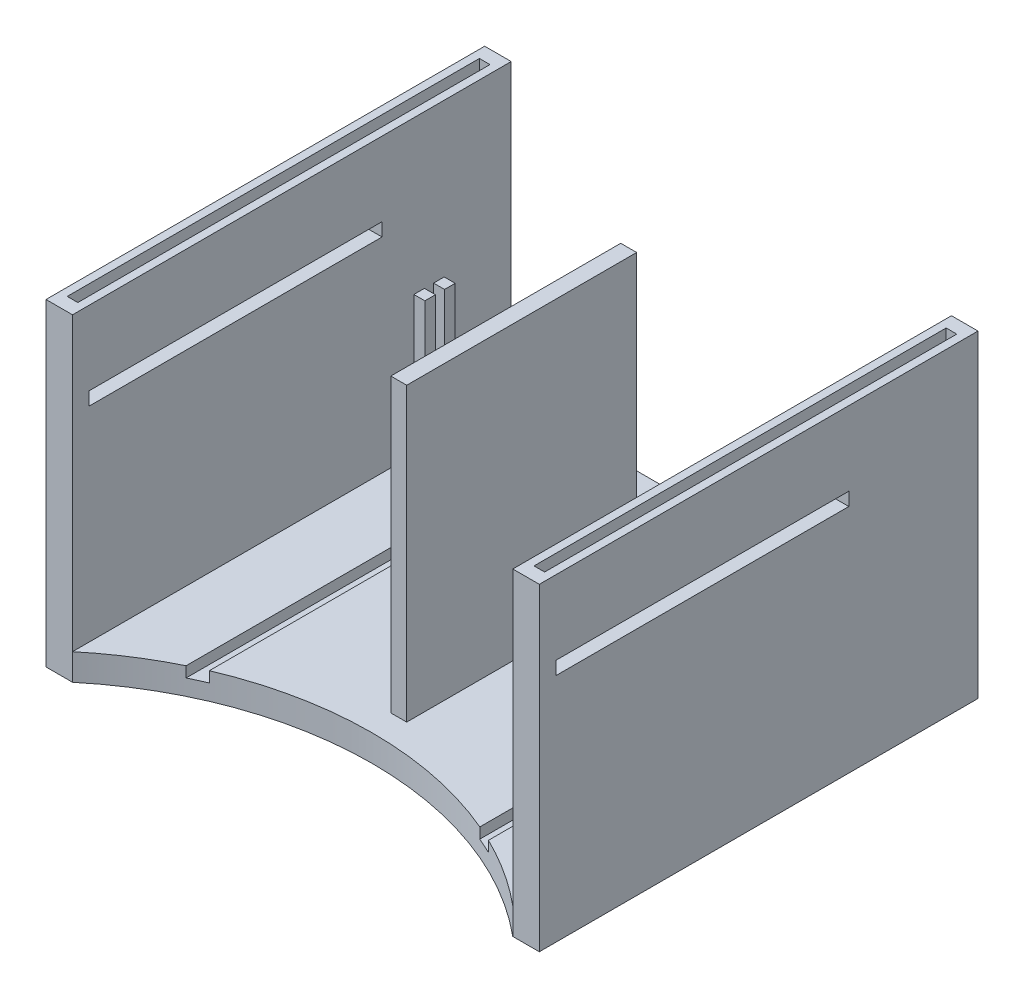
SolidWorks part; units mm, degrees
ref_plane "Front Plane" through (0, 0, 0) normal (0, 0, 1) x (1, 0, 0)
ref_plane "Top Plane" through (0, 0, 0) normal (0, 1, 0) x (1, 0, 0)
ref_plane "Right Plane" through (0, 0, 0) normal (1, 0, 0) x (0, 0, -1)
sketch "Sketch2" plane through (0, 0, 0) normal (0, 0, 1) x (1, 0, 0)
  line L0 (0, 0) -> (186, 0)
  line L1 (186, 0) -> (186, 120)
  line L2 (0, 0) -> (0, 120)
  dimension "D1" = 120
  dimension "D2" = 186
extrude "Extrude-Thin2" add sketch "Sketch2" along normal blind 165.4 thin thin type one direction wall 10
sketch "Sketch11" plane through (0, 10, 0) normal (0, 1, 0) x (1, 0, 0)
  line L0 (10, -165.4) -> (10, 0) construction
  line L1 (10, -32.703) -> (176, -32.703)
  line L2 (10, -32.703) -> (10, -36.703)
  line L3 (10, -36.703) -> (176, -36.703)
  line L4 (176, -32.703) -> (176, -36.703)
  line L6 (176, 0) -> (10, 0) construction
  dimension "D1" = 32.703
  dimension "D2" = 4
  dimension "D3" = 166
  dimension "D4" = 0
extrude "Boss-Extrude3" add sketch "Sketch11" along normal blind 2.6416
sketch "Sketch13" plane through (10, 0, 0) normal (1, 0, 0) x (0, 0, -1)
  line L0 (0, 120) -> (0, 0) construction
  line L1 (-159.195, 92.0516) -> (-48.7, 92.0516)
  line L2 (-159.195, 92.0516) -> (-159.195, 87.0516)
  line L3 (-159.195, 87.0516) -> (-48.7, 87.0516)
  line L4 (-48.7, 92.0516) -> (-48.7, 87.0516)
  line L6 (-165.4, 120) -> (-165.4, 0) construction
  line L7 (-165.4, 120) -> (0, 120) construction
  dimension "D1" = 5
  dimension "D2" = 6.205
  dimension "D3" = 48.7
  dimension "D4" = 27.9484
extrude "Cut-Extrude6" cut sketch "Sketch13" against normal through all both and the other way through all
sketch "Sketch14" plane through (0, 10, 0) normal (0, 1, 0) x (1, 0, 0)
  line L0 (176, -165.4) -> (10, -165.4)
  line L1 (93, -135.4) -> (10, -135.4) construction
  line L2 (10, -165.4) -> (10, -36.703) construction
  arc A0 (10, -165.4) -> (176, -165.4) centre (93, -265.2167) cw
  dimension "D1" = 30
extrude "Cut-Extrude7" cut sketch "Sketch14" against normal through all
sketch "Sketch19" plane through (0, 120, 0) normal (0, 1, 0) x (1, 0, 0)
  line L0 (10, -165.4) -> (10, -36.703) construction
  line L1 (3, -5) -> (7, -5)
  line L2 (3, -5) -> (3, -160.4)
  line L3 (3, -160.4) -> (7, -160.4)
  line L4 (7, -5) -> (7, -160.4)
  line L5 (0, -165.4) -> (0, 0) construction
  line L6 (0, 0) -> (10, 0) construction
  line L7 (0, -165.4) -> (10, -165.4) construction
  point P9 (5, 0)
  point P12 (5, -165.4)
  dimension "D1" = 3
  dimension "D2" = 3
  dimension "D3" = 5
  dimension "D4" = 5
extrude "Cut-Extrude9" cut sketch "Sketch19" against normal blind 10
sketch "Sketch20" plane through (0, 120, 0) normal (0, 1, 0) x (1, 0, 0)
  line L0 (186, -165.4) -> (186, 0) construction
  line L1 (179, -5) -> (183, -5)
  line L2 (179, -5) -> (179, -160.4)
  line L3 (179, -160.4) -> (183, -160.4)
  line L4 (183, -5) -> (183, -160.4)
  line L5 (176, -165.4) -> (176, 0) construction
  line L6 (176, 0) -> (186, 0) construction
  line L7 (176, -165.4) -> (186, -165.4) construction
  point P9 (181, 0)
  point P12 (181, -165.4)
  dimension "D1" = 3
  dimension "D2" = 3
  dimension "D3" = 5
  dimension "D4" = 5
extrude "Cut-Extrude10" cut sketch "Sketch20" against normal blind 10
sketch "Sketch21" plane through (0, 10, 0) normal (0, 1, 0) x (1, 0, 0)
  line L0 (176, -165.4) -> (176, -36.703) construction
  line L1 (90, -38.703) -> (96, -38.703)
  line L2 (90, -38.703) -> (90, -125.4)
  line L3 (90, -125.4) -> (96, -125.4)
  line L4 (96, -38.703) -> (96, -125.4)
  line L5 (10, -165.4) -> (10, 0) construction
  line L7 (10, -159.195) -> (10, -48.7) construction
  line L8 (10, -119.195) -> (176, -119.195) construction
  line L9 (10, -165.4) -> (10, -36.703) construction
  line L10 (0, -165.4) -> (10, -165.4) construction
  line L11 (10, -36.703) -> (176, -36.703) construction
  dimension "D1" = 80
  dimension "D2" = 80
  dimension "D3" = 40
  dimension "D4" = 46.205
  dimension "D5" = 2
extrude "Boss-Extrude4" add sketch "Sketch21" along direction (0, 1, 0) on the side of the normal through all
sketch "Sketch22" plane through (0, 10, 0) normal (0, 1, 0) x (1, 0, 0)
  line L0 (36, -48.703) -> (36, -148.5832)
  line L1 (36, -148.5832) -> (42, -145.8376)
  line L2 (42, -145.8376) -> (42, -48.703)
  line L3 (42, -48.703) -> (36, -48.703)
  line L4 (10, -36.703) -> (176, -36.703) construction
  line L6 (10, -159.195) -> (10, -48.7) construction
  line L7 (144, -145.8376) -> (150, -148.5832)
  line L8 (150, -148.5832) -> (150, -48.703)
  line L9 (150, -48.703) -> (144, -48.703)
  line L10 (144, -48.703) -> (144, -145.8376)
  line L11 (176, -165.4) -> (176, -36.703) construction
  arc A0 (176, -165.4) -> (10, -165.4) centre (93, -265.2167) ccw construction
  dimension "D1" = 6
  dimension "D2" = 26
  dimension "D3" = 6
  dimension "D4" = 26
  dimension "D5" = 12
extrude "Cut-Extrude11" cut sketch "Sketch22" against normal blind 4
sketch "Sketch23" plane through (0, 10, 0) normal (0, 1, 0) x (1, 0, 0)
  line L0 (10, -32.703) -> (10, 0) construction
  line L1 (10, -25.263) -> (176, -25.263)
  line L2 (10, -25.263) -> (10, -29.263)
  line L3 (10, -29.263) -> (176, -29.263)
  line L4 (176, -25.263) -> (176, -29.263)
  line L8 (176, -32.703) -> (10, -32.703) construction
  dimension "D1" = 3.44
  dimension "D2" = 166
  dimension "D3" = 0
  dimension "D4" = 4
extrude "Boss-Extrude5" add sketch "Sketch23" along normal blind 2.6416
sketch "Sketch24" plane through (0, 12.6416, 0) normal (0, 1, 0) x (1, 0, 0)
  line L0 (10, -29.263) -> (176, -29.263) construction
  line L1 (10, -25.263) -> (14.14, -25.263)
  line L2 (10, -25.263) -> (10, -29.263)
  line L3 (10, -29.263) -> (14.14, -29.263)
  line L4 (14.14, -25.263) -> (14.14, -29.263)
  dimension "D1" = 4.14
extrude "Boss-Extrude6" add sketch "Sketch24" along normal blind 49.64
sketch "Sketch25" plane through (0, 12.6416, 0) normal (0, 1, 0) x (1, 0, 0)
  line L0 (14.14, -29.263) -> (176, -29.263) construction
  line L1 (176, -25.263) -> (171.86, -25.263)
  line L2 (176, -25.263) -> (176, -29.263)
  line L3 (176, -29.263) -> (171.86, -29.263)
  line L4 (171.86, -25.263) -> (171.86, -29.263)
  dimension "D1" = 4.14
extrude "Boss-Extrude7" add sketch "Sketch25" along normal blind 49.64
sketch "Sketch26" plane through (0, 12.6416, 0) normal (0, 1, 0) x (1, 0, 0)
  line L0 (10, -36.703) -> (176, -36.703) construction
  line L1 (10, -32.703) -> (14.14, -32.703)
  line L2 (10, -32.703) -> (10, -36.703)
  line L3 (10, -36.703) -> (14.14, -36.703)
  line L4 (14.14, -32.703) -> (14.14, -36.703)
  dimension "D1" = 4.14
extrude "Boss-Extrude8" add sketch "Sketch26" along normal blind 49.64
sketch "Sketch27" plane through (0, 12.6416, 0) normal (0, 1, 0) x (1, 0, 0)
  line L0 (14.14, -36.703) -> (176, -36.703) construction
  line L1 (176, -32.703) -> (171.86, -32.703)
  line L2 (176, -32.703) -> (176, -36.703)
  line L3 (176, -36.703) -> (171.86, -36.703)
  line L4 (171.86, -32.703) -> (171.86, -36.703)
  dimension "D1" = 4.14
extrude "Boss-Extrude9" add sketch "Sketch27" along normal blind 49.64
